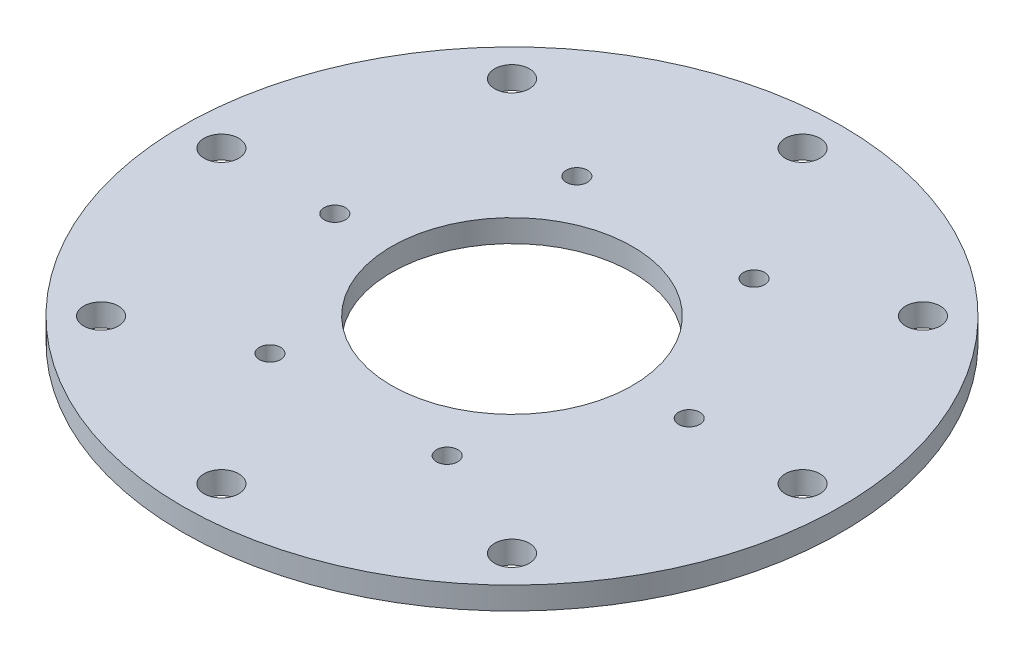
SolidWorks part; units mm, degrees
material "1060 Alloy"
ref_plane "Front Plane" through (0, 0, 0) normal (0, 0, 1) x (1, 0, 0)
ref_plane "Top Plane" through (0, 0, 0) normal (0, 1, 0) x (1, 0, 0)
ref_plane "Right Plane" through (0, 0, 0) normal (1, 0, 0) x (0, 0, -1)
sketch "Sketch2" plane through (0, 0, 0) normal (0, 1, 0) x (1, 0, 0)
  circle A0 centre (0, 0) radius 17
  circle A1 centre (0, 0) radius 46.5
  circle A2 centre (0, 0) radius 41 construction
  circle A3 centre (-41, 0) radius 2.45
  circle A4 centre (0, 0) radius 25 construction
  circle A5 centre (-25, 0) radius 1.5
  circle A6 centre (-12.5, 21.6506) radius 1.5
  circle A7 centre (12.5, 21.6506) radius 1.5
  circle A8 centre (25, 0) radius 1.5
  circle A9 centre (12.5, -21.6506) radius 1.5
  circle A10 centre (-12.5, -21.6506) radius 1.5
  circle A11 centre (-28.9914, 28.9914) radius 2.45
  circle A12 centre (0, 41) radius 2.45
  circle A13 centre (28.9914, 28.9914) radius 2.45
  circle A14 centre (41, 0) radius 2.45
  circle A15 centre (28.9914, -28.9914) radius 2.45
  circle A16 centre (0, -41) radius 2.45
  circle A17 centre (-28.9914, -28.9914) radius 2.45
  point P22 (0, 0)
  point P33 (0, 0)
  dimension "D1" = 3
  dimension "D2" = 50
  dimension "D4" = 34
  dimension "D5" = 93
  dimension "D6" = 82
  dimension "D7" = 4.9
  dimension "D3" = 6
  dimension "D8" = 8
extrude "Boss-Extrude1" add sketch "Sketch2" along normal blind 3.175
equation "\"Stator_OD\"= 60'No Tolerance given"
equation "\"A\"=35.81 'taken off spec sheet for 06808 (A)"
equation "\"Rotor_ID\"= 30'No Tolerance Given"
equation "\"back_bearing_Thickness\"= 5'-0.12"
equation "\"back_bearing_OD\"= 24'-0.009 https://www.mcmaster.com/5972K155/"
equation "\"Stator_Gap\"= 0.0375'+- 0.0125 (From 1.3.3.1 Kollmorgen manual)"
equation "\"Back_mount_hole\"= 1.75'To be tapped to M2 (USE LOCKTITE)"
equation "\"facePlate_Mount_Hole\"= 2.75'To be tapped to M3"
equation "\"final_shaftD\"= 12'To fit in harmonic"
equation "\"final_shaftL\"= 5.25+3+\"sheet_thick\"+\"connector_thick\"-3+\"harmon_coupleL\"+0.5-\"shaft_Ladjust\"'length to make everything nice and aligned"
equation "\"back_bearing_ID\"= 15'"
equation "\"back_bearing_IDOD\"= 16.5'measured off CAD, actually 16.75, but rounded down to nicer number"
equation "\"rotor_shaftD\"= \"Rotor_ID\" - (\"rotor-shaft_gap\")*2'"
equation "\"front_bearing_ID\"= 12'https://www.mcmaster.com/5972K154/"
equation "\"front_bearing_OD\"= 21'-0.009"
equation "\"front_bearing_IDOD\"= 13.5'Measured off CAD. Actually 13.75, but rounded down"
equation "\"rotor-shaft_gap\" = 0.0185 '+-0.0065 (from manual)"
equation "\"front_bearing_Thickness\"= 5'-0.12"
equation "\"rotor_thickness\"= 2.4'measured off CAD"
equation "\"rotor_height\"= 32.86'+-0.075 taken off spec sheet for 06826 (C)"
equation "\"B\"= 26.3'+-0.35 taken off spec sheet for 06826"
equation "\"key_L\"= 20'-0.2 https://www.mcmaster.com/2977N19/"
equation "\"key_H\"= 4'-0.03"
equation "\"key_W\"= 4'-0.03"
equation "\"harmon_keyH\"= 13.8'+0.1 from drawing"
equation "\"harmon_coupleL\"= 21.5' taken from drawing https://www.harmonicdrive.net/_hd/content/caddownloads/dxf/csg-2uh-lw_gearheads/csg-20-100-2uh-lw.pdf"
equation "\"harmon_diam\"= 93' from drawing"
equation "\"harmon_BCD\"= 82' from drawing"
equation "\"harmon_holeD1\"= 5.5' from drawing"
equation "\"harmon_holeD2\"= 5' from drawing"
equation "\"harmon_holeAng\"= 22.5' from drawing"
equation "\"sheet_thick\"= 1/8*25.4 'random, replace w actual sheet thickness when u feel like :)"
equation "\"D1@Sketch2\"=\"facePlate_Mount_Hole\"+0.25"
equation "\"D4@Sketch2\"=\"back_bearing_OD\"+10"
equation "\"D5@Sketch2\"=\"harmon_diam\""
equation "\"D6@Sketch2\"=\"harmon_BCD\""
equation "\"D7@Sketch2\"=\"harmon_holeD2\"-0.1"
equation "\"D1@Boss-Extrude1\"=\"sheet_thick\""
equation "\"nut-thickness\"= 5 'idk measure the ones in the shop and adjust"
equation "\"connector_thick\"= 10' random for now"
equation "\"shaft_Ladjust\"= 6.5' sorry. It's silly, but it works."
